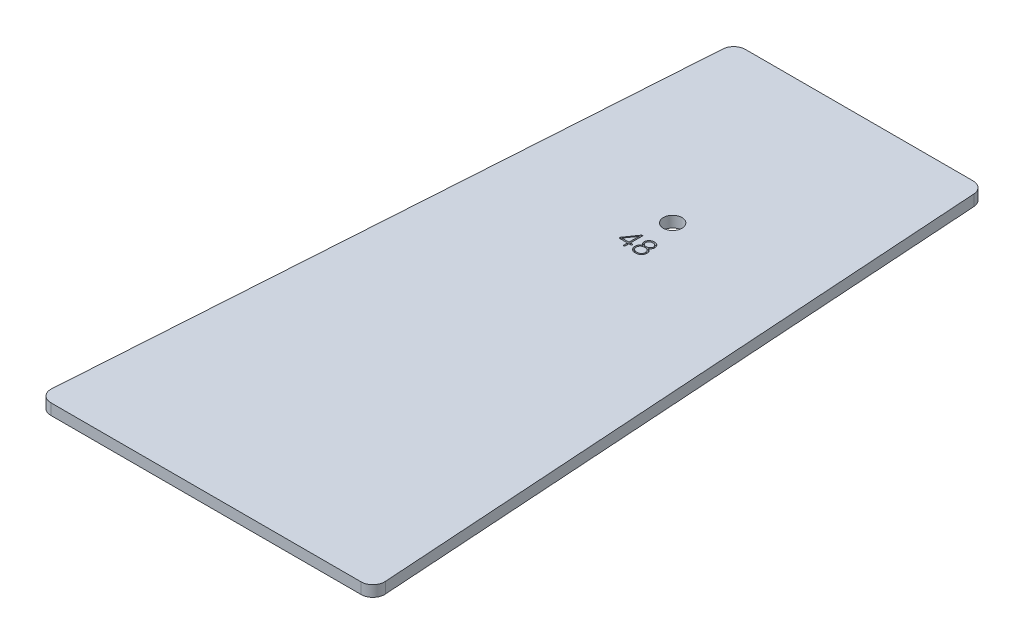
SolidWorks part; units mm, degrees
material "Acrylic (Medium-high impact)"
ref_plane "Front Plane" through (0, 0, 0) normal (0, 0, 1) x (1, 0, 0)
ref_plane "Top Plane" through (0, 0, 0) normal (0, 1, 0) x (1, 0, 0)
ref_plane "Right Plane" through (0, 0, 0) normal (1, 0, 0) x (0, 0, -1)
sketch "Sketch1" plane through (0, 0, 0) normal (0, 1, 0) x (1, 0, 0)
  line L0 (0, 0) -> (0, -355.6) construction
  line L1 (-67.945, 0) -> (67.945, 0)
  line L2 (67.945, 0) -> (91.2523, -355.6)
  line L3 (91.2523, -355.6) -> (-91.2523, -355.6)
  line L4 (-67.945, 0) -> (-91.2523, -355.6)
  dimension "D1" = 355.6
  dimension "D2" = 7.5
  dimension "D3" = 135.89
extrude "Boss-Extrude1" add sketch "Sketch1" along normal blind 5.9944
sketch "Sketch2" plane through (0, 5.9944, 0) normal (0, 1, 0) x (1, 0, 0)
  line L0 (0, 0) -> (0, -101.6) construction
  line L1 (67.945, 0) -> (-67.945, 0) construction
  circle A0 centre (0, -101.6) radius 5.08
  dimension "D1" = 10.16
  dimension "D2" = 101.6
extrude "Cut-Extrude1" cut sketch "Sketch2" against normal through all
sketch "Sketch3" plane through (0, 5.9944, 0) normal (0, 1, 0) x (1, 0, 0)
  line L1 (0, -101.6) -> (0, -114.3) construction
  line L2 (7.62, -125.73) -> (7.62, -114.3) construction
  line L3 (7.62, -125.73) -> (-7.62, -125.73) construction
  line L4 (7.62, -114.3) -> (-7.62, -114.3) construction
  line L5 (-7.62, -125.73) -> (-7.62, -114.3) construction
  line L6 (7.62, -125.73) -> (-7.62, -114.3) construction
  line L7 (7.62, -114.3) -> (-7.62, -125.73) construction
  text T0 "48"
  point P7 (0, -120.015)
  dimension "D1" = 12.7
  dimension "D2" = 11.43
  dimension "D3" = 15.24
extrude "Cut-Extrude2" cut sketch "Sketch3" against normal blind 1.27
fillet "Fillet1" radius 6.35 4 edges at (-91.2523, 2.9972, 355.6) (91.2523, 2.9972, 355.6) (67.945, 2.9972, 0) (-67.945, 2.9972, 0)
